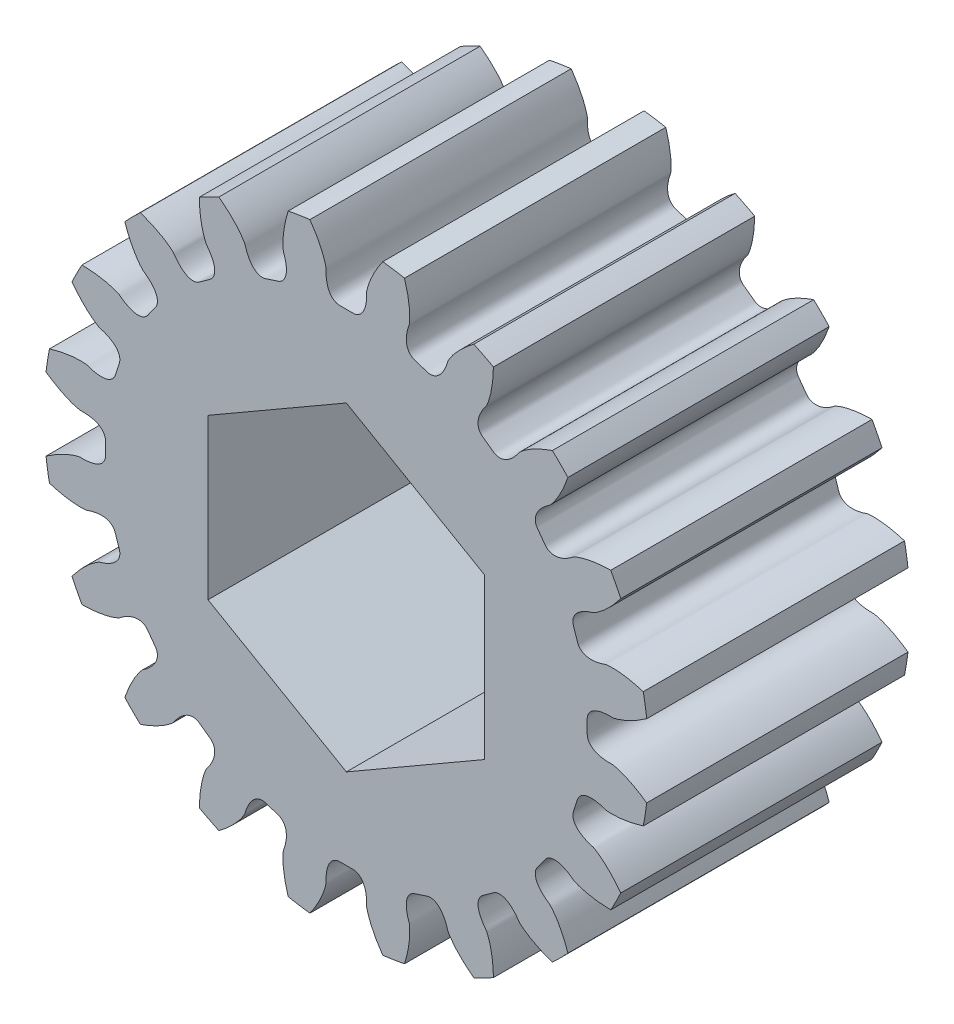
SolidWorks part; units mm, degrees
ref_plane "Front Plane" through (0, 0, 0) normal (0, 0, 1) x (1, 0, 0)
ref_plane "Top Plane" through (0, 0, 0) normal (0, 1, 0) x (1, 0, 0)
ref_plane "Right Plane" through (0, 0, 0) normal (1, 0, 0) x (0, 0, -1)
ref_plane "Plane4" through (0, 0, -6.0325) normal (0, 0, -1) x (-1, 0, 0)
sketch "Sketch1" plane through (0, 0, -6.0325) normal (0, 0, -1) x (-1, 0, 0)
  arc A0 (-9.5127, 10.2308) -> (-10.2308, 9.5127) centre (0, 0) ccw
  arc A1 (-12.2086, 6.7905) -> (-12.6697, 5.8856) centre (0, 0) ccw
  arc A2 (-13.7094, 2.6855) -> (-13.8683, 1.6824) centre (0, 0) ccw
  arc A3 (-13.8683, -1.6824) -> (-13.7094, -2.6855) centre (0, 0) ccw
  arc A4 (-12.6697, -5.8856) -> (-12.2086, -6.7905) centre (0, 0) ccw
  arc A5 (-10.2308, -9.5127) -> (-9.5127, -10.2308) centre (0, 0) ccw
  arc A6 (-6.7905, -12.2086) -> (-5.8856, -12.6697) centre (0, 0) ccw
  arc A7 (-2.6855, -13.7094) -> (-1.6824, -13.8683) centre (0, 0) ccw
  arc A8 (1.6824, -13.8683) -> (2.6855, -13.7094) centre (0, 0) ccw
  arc A9 (5.8856, -12.6697) -> (6.7905, -12.2086) centre (0, 0) ccw
  arc A10 (9.5127, -10.2308) -> (10.2308, -9.5127) centre (0, 0) ccw
  arc A11 (12.2086, -6.7905) -> (12.6697, -5.8856) centre (0, 0) ccw
  arc A12 (13.7094, -2.6855) -> (13.8683, -1.6824) centre (0, 0) ccw
  arc A13 (13.8683, 1.6824) -> (13.7094, 2.6855) centre (0, 0) ccw
  arc A14 (12.6697, 5.8856) -> (12.2086, 6.7905) centre (0, 0) ccw
  arc A15 (10.2308, 9.5127) -> (9.5127, 10.2308) centre (0, 0) ccw
  arc A16 (6.7905, 12.2086) -> (5.8856, 12.6697) centre (0, 0) ccw
  arc A17 (2.6855, 13.7094) -> (1.6824, 13.8683) centre (0, 0) ccw
  arc A18 (-1.6824, 13.8683) -> (-2.6855, 13.7094) centre (0, 0) ccw
  arc A19 (-5.8856, 12.6697) -> (-6.7905, 12.2086) centre (0, 0) ccw
  spline S0 degree 3 number of poles 113 (-12.2086, 6.7905) -> (-10.2308, 9.5127)
  spline S1 degree 3 number of poles 113 (-13.7094, 2.6855) -> (-12.6697, 5.8856)
  spline S2 degree 3 number of poles 113 (-13.8683, -1.6824) -> (-13.8683, 1.6824)
  spline S3 degree 3 number of poles 113 (-12.6697, -5.8856) -> (-13.7094, -2.6855)
  spline S4 degree 3 number of poles 113 (-10.2308, -9.5127) -> (-12.2086, -6.7905)
  spline S5 degree 3 number of poles 113 (-6.7905, -12.2086) -> (-9.5127, -10.2308)
  spline S6 degree 3 number of poles 113 (-2.6855, -13.7094) -> (-5.8856, -12.6697)
  spline S7 degree 3 number of poles 113 (1.6824, -13.8683) -> (-1.6824, -13.8683)
  spline S8 degree 3 number of poles 113 (5.8856, -12.6697) -> (2.6855, -13.7094)
  spline S9 degree 3 number of poles 113 (9.5127, -10.2308) -> (6.7905, -12.2086)
  spline S10 degree 3 number of poles 113 (12.2086, -6.7905) -> (10.2308, -9.5127)
  spline S11 degree 3 number of poles 113 (13.7094, -2.6855) -> (12.6697, -5.8856)
  spline S12 degree 3 number of poles 113 (13.8683, 1.6824) -> (13.8683, -1.6824)
  spline S13 degree 3 number of poles 113 (12.6697, 5.8856) -> (13.7094, 2.6855)
  spline S14 degree 3 number of poles 113 (10.2308, 9.5127) -> (12.2086, 6.7905)
  spline S15 degree 3 number of poles 113 (6.7905, 12.2086) -> (9.5127, 10.2308)
  spline S16 degree 3 number of poles 113 (2.6855, 13.7094) -> (5.8856, 12.6697)
  spline S17 degree 3 number of poles 113 (-1.6824, 13.8683) -> (1.6824, 13.8683)
  spline S18 degree 3 number of poles 113 (-5.8856, 12.6697) -> (-2.6855, 13.7094)
  spline S19 degree 3 number of poles 113 (-9.5127, 10.2308) -> (-6.7905, 12.2086)
extrude "Boss-Extrude1" add sketch "Sketch1" against normal blind 12.065
sketch "Sketch2" plane through (0, 0, -6.0325) normal (0, 0, -1) x (-1, 0, 0)
  circle A0 centre (0, 0) radius 8.89
extrude "Boss-Extrude2" add sketch "Sketch2" along normal blind 0.2921
sketch "Sketch3" plane through (0, 0, 6.0325) normal (0, 0, 1) x (1, 0, 0)
  circle A0 centre (0, 0) radius 8.89
extrude "Boss-Extrude3" add sketch "Sketch3" along normal blind 0.2921
sketch "Sketch4" plane through (0, 0, 6.3246) normal (0, 0, 1) x (1, 0, 0)
  line L0 (6.3881, -3.6882) -> (6.3881, 3.6882)
  line L1 (6.3881, 3.6882) -> (0, 7.3763)
  line L2 (0, 7.3763) -> (-6.3881, 3.6882)
  line L3 (-6.3881, 3.6882) -> (-6.3881, -3.6882)
  line L4 (-6.3881, -3.6882) -> (0, -7.3763)
  line L5 (0, -7.3763) -> (6.3881, -3.6882)
extrude "Cut-Extrude1" cut sketch "Sketch4" against normal through all
ref_plane "Plane5" through (0, 8.89, 0) normal (0, 1, 0) x (1, 0, 0)
sketch "Sketch5" plane through (0, 8.89, 0) normal (0, 1, 0) x (1, 0, 0)
  line L1 (-10.2308, -6.0325) -> (10.0897, -6.0325)
  line L2 (-10.2308, -6.0325) -> (-10.2308, -6.404)
  line L3 (-10.2308, -6.404) -> (10.0897, -6.404)
  line L4 (10.0897, -6.0325) -> (10.0897, -6.404)
extrude "Cut-Extrude2" cut sketch "Sketch5" against normal through all
